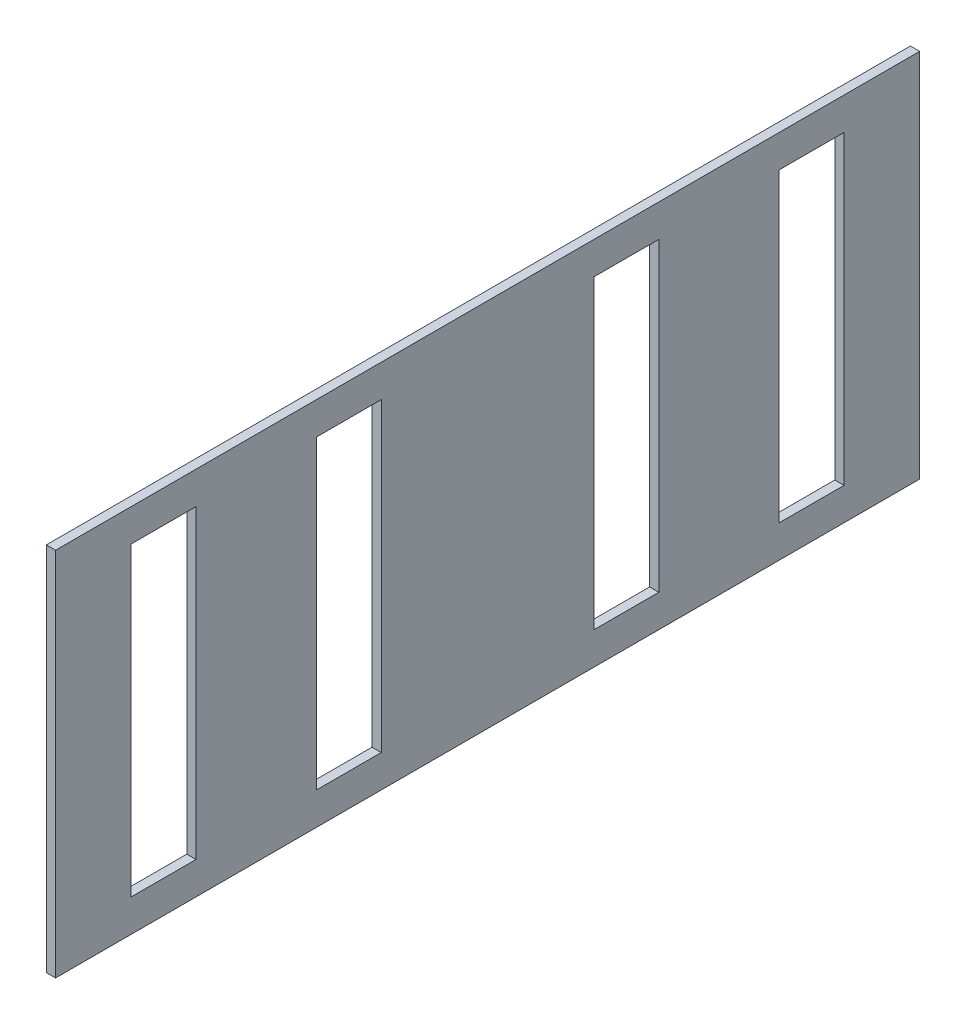
SolidWorks part; units mm, degrees
ref_plane "Front Plane" through (0, 0, 0) normal (0, 0, 1) x (1, 0, 0)
ref_plane "Top Plane" through (0, 0, 0) normal (0, 1, 0) x (1, 0, 0)
ref_plane "Right Plane" through (0, 0, 0) normal (1, 0, 0) x (0, 0, -1)
sketch "Sketch1" plane through (0, 0, 0) normal (1, 0, 0) x (0, 0, -1)
  line L0 (88.8651, 0) -> (88.8651, 29.1273) construction
  line L1 (-118.491, 50.8) -> (118.491, 50.8)
  line L2 (-118.491, 50.8) -> (-118.491, -50.8)
  line L3 (-118.491, -50.8) -> (118.491, -50.8)
  line L4 (118.491, 50.8) -> (118.491, -50.8)
  line L5 (-118.491, 50.8) -> (118.491, -50.8) construction
  line L6 (-118.491, -50.8) -> (118.491, 50.8) construction
  line L7 (38.0651, 0) -> (38.0651, 33.6403) construction
  line L8 (76.1301, 0) -> (0, 0) construction
  line L9 (79.9751, 41.91) -> (97.7551, 41.91)
  line L10 (79.9751, 41.91) -> (79.9751, -41.91)
  line L11 (79.9751, -41.91) -> (97.7551, -41.91)
  line L12 (97.7551, 41.91) -> (97.7551, -41.91)
  line L13 (79.9751, 41.91) -> (97.7551, -41.91) construction
  line L14 (79.9751, -41.91) -> (97.7551, 41.91) construction
  line L15 (0, 0) -> (0, 37.9656) construction
  line L16 (29.1751, 41.91) -> (46.9551, 41.91)
  line L17 (29.1751, 41.91) -> (29.1751, -41.91)
  line L18 (29.1751, -41.91) -> (46.9551, -41.91)
  line L19 (46.9551, 41.91) -> (46.9551, -41.91)
  line L20 (29.1751, 41.91) -> (46.9551, -41.91) construction
  line L21 (29.1751, -41.91) -> (46.9551, 41.91) construction
  line L22 (-79.9751, 41.91) -> (-97.7551, 41.91)
  line L23 (-79.9751, 41.91) -> (-79.9751, -41.91)
  line L24 (-97.7551, 41.91) -> (-97.7551, -41.91)
  line L25 (-79.9751, -41.91) -> (-97.7551, -41.91)
  line L26 (-46.9551, 41.91) -> (-46.9551, -41.91)
  line L27 (-29.1751, -41.91) -> (-46.9551, -41.91)
  line L28 (-29.1751, 41.91) -> (-29.1751, -41.91)
  line L29 (-29.1751, 41.91) -> (-46.9551, 41.91)
  point P0 (0, 0)
  dimension "D1" = 101.6
  dimension "D2" = 236.982
  dimension "D3" = 17.78
  dimension "D4" = 83.82
  dimension "D5" = 50.8
extrude "Boss-Extrude1" add sketch "Sketch1" along normal blind 2.54
